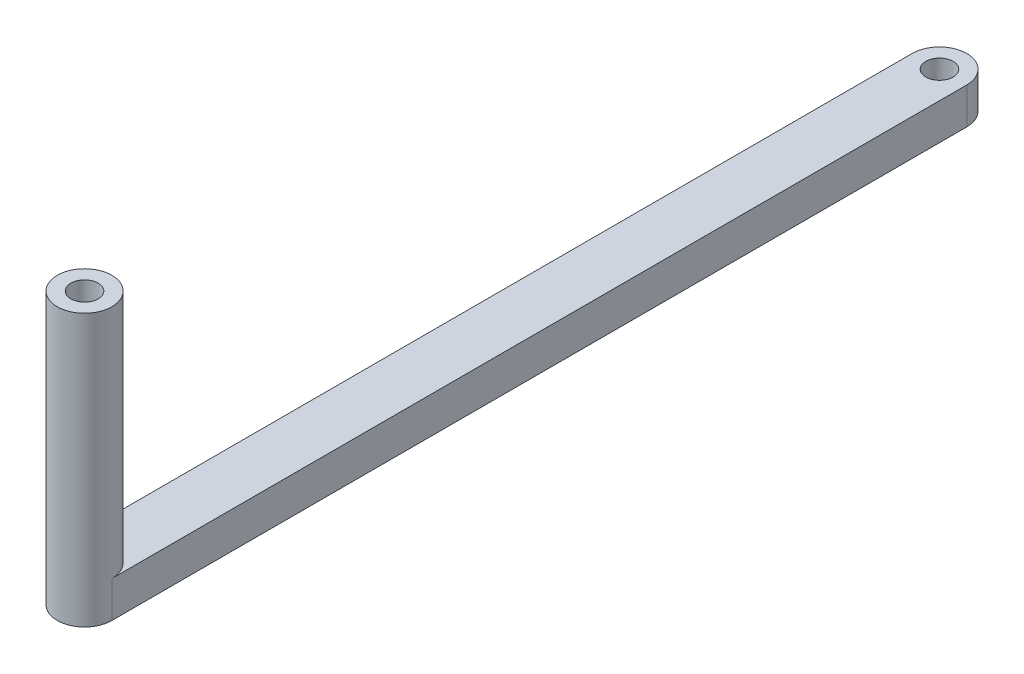
SolidWorks part; units mm, degrees
ref_plane "Front Plane" through (0, 0, 0) normal (0, 0, 1) x (1, 0, 0)
ref_plane "Top Plane" through (0, 0, 0) normal (0, 1, 0) x (1, 0, 0)
ref_plane "Right Plane" through (0, 0, 0) normal (1, 0, 0) x (0, 0, -1)
sketch "Sketch1" plane through (0, 0, 0) normal (0, 1, 0) x (1, 0, 0)
  line L0 (0, 0) -> (0, 47)
  line L1 (3, 47) -> (3, 0)
  arc A0 (0, 47) -> (3, 47) centre (1.5, 47) cw
  arc A1 (3, 0) -> (0, 0) centre (1.5, 0) cw
  circle A2 centre (1.5, 0) radius 0.75
  circle A3 centre (1.5, 47) radius 0.75
  point P6 (1.5, -1.5)
  point P8 (1.5, 48.5)
  dimension "D3" = 1.5
  dimension "D4" = 1.5
  dimension "D1" = 3
  dimension "D2" = 50
extrude "Boss-Extrude2" add sketch "Sketch1" along normal blind 2
sketch "Sketch2" plane through (0, 2, 0) normal (0, 1, 0) x (1, 0, 0)
  circle A0 centre (1.5, 0) radius 1.5
  circle A1 centre (1.5, 0) radius 0.75
extrude "Boss-Extrude3" add sketch "Sketch2" along normal blind 12.94
